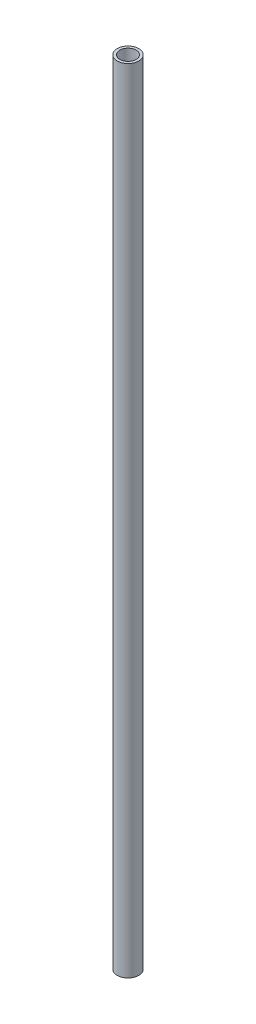
SolidWorks part; units mm, degrees
material "PTFE (general)"
ref_plane "Alzado" through (0, 0, 0) normal (0, 0, 1) x (1, 0, 0)
ref_plane "Planta" through (0, 0, 0) normal (0, 1, 0) x (1, 0, 0)
ref_plane "Vista lateral" through (0, 0, 0) normal (1, 0, 0) x (0, 0, -1)
sketch "Sketch1" plane through (0, 0, 0) normal (0, 0, 1) x (1, 0, 0)
  line L0 (1.25, -39) -> (1.65, -39)
  line L1 (1.65, -39) -> (1.65, -160.4)
  line L2 (1.65, -160.4) -> (1.25, -160.4)
  line L3 (1.25, -160.4) -> (1.25, -39)
  line L4 (0, -164.4) -> (0, -35) construction
revolve "Funda_PTFE" add sketch "Sketch1" angle 360 about L4
